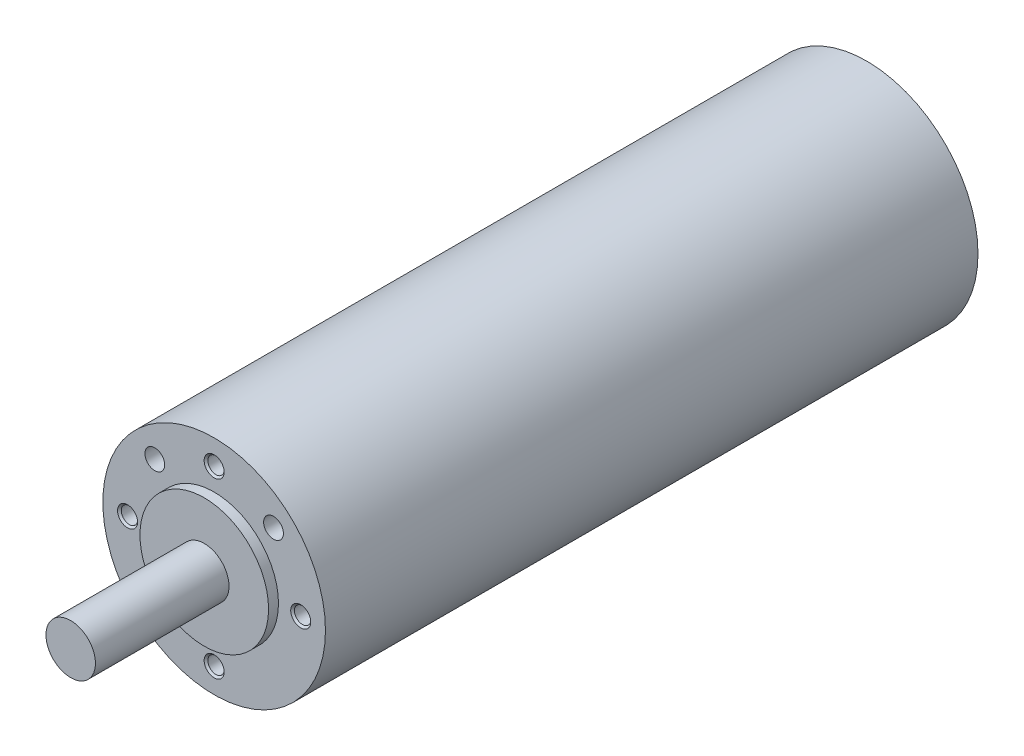
SolidWorks part; units mm, degrees
ref_plane "Front Plane" through (0, 0, 0) normal (0, 0, 1) x (1, 0, 0)
ref_plane "Top Plane" through (0, 0, 0) normal (0, 1, 0) x (1, 0, 0)
ref_plane "Right Plane" through (0, 0, 0) normal (1, 0, 0) x (0, 0, -1)
sketch "Sketch1" plane through (0, 0, 0) normal (0, 0, 1) x (1, 0, 0)
  circle A0 centre (0, 0) radius 22.5
  dimension "D1" = 45
extrude "Boss-Extrude1" add sketch "Sketch1" against normal blind 131.9
sketch "Sketch2" plane through (0, 0, 0) normal (0, 0, 1) x (1, 0, 0)
  circle A0 centre (0, 0) radius 13
  dimension "D1" = 26
extrude "Boss-Extrude2" add sketch "Sketch2" along normal blind 2
sketch "Sketch3" plane through (0, 0, 2) normal (0, 0, 1) x (1, 0, 0)
  circle A0 centre (0, 0) radius 5
  dimension "D1" = 10
extrude "Boss-Extrude3" add sketch "Sketch3" along normal blind 27
sketch "Sketch4" plane through (0, 0, 0) normal (0, 0, 1) x (1, 0, 0)
  circle A0 centre (0, 0) radius 17.5 construction
  circle A1 centre (0, 17.5) radius 2
  circle A2 centre (0, 0) radius 17.5 construction
  circle A3 centre (0, 0) radius 17.5 construction
  circle A4 centre (0, 0) radius 17.5 construction
  circle A5 centre (17.5, 0) radius 2
  circle A6 centre (0, -17.5) radius 2
  circle A7 centre (-17.5, 0) radius 2
  point P14 (0, 0)
  point P21 (0, 0)
  dimension "D1" = 35
  dimension "D2" = 4
  dimension "D3" = 4
  dimension "D4" = 4
hole_wizard "M4 Tapped Hole1" positions "Sketch5" profile "Sketch6" tap size "M4" standard "ISO"
sketch "Sketch5" plane through (0, 0, 0) normal (0, 0, 1) x (1, 0, 0)
  point P0 (0, 17.5)
  point P3 (-17.5, 0)
  point P6 (0, -17.5)
  point P9 (17.5, 0)
sketch "Sketch6" plane through (0, 17.5, 0) normal (1, 0, 0) x (0, -1, 0)
  line L0 (0, 0) -> (0, 9.9914)
  line L1 (0, 9.9914) -> (1.65, 9)
  line L2 (1.65, 9) -> (1.65, 0.375)
  line L3 (1.65, 0.375) -> (2.025, 0)
  line L5 (2.025, 0) -> (0, 0)
  line L6 (-1.65, 0.375) -> (-2.025, 0) construction
  line L10 (0, 9.9914) -> (-1.65, 9) construction
  line L11 (0, -6.35) -> (0, 107.95) construction
  dimension "Tap Drill Dia." = 3.3
  dimension "Tap Drill Depth" = 9
  dimension "Near C'Sink Dia." = 4.05
  dimension "Near C'Sink Angle" = 90
  dimension "Drill Angle" = 118
cosmetic thread "Hole Thread1" parameters "D1"=8, "D2"=4
cosmetic thread "Hole Thread2" parameters "D1"=8, "D2"=4
cosmetic thread "Hole Thread3" parameters "D1"=8, "D2"=4
cosmetic thread "Hole Thread4" parameters "D1"=8, "D2"=4
sketch "Sketch7" plane through (0, 0, 0) normal (0, 0, 1) x (1, 0, 0)
  circle A2 centre (0, 0) radius 17.5 construction
  circle A3 centre (-12, 12.7377) radius 2
  circle A4 centre (12, 12.7377) radius 2
  dimension "D1" = 35
  dimension "D3" = 4
  dimension "D4" = 4
  dimension "D2" = 12
  dimension "D5" = 12
extrude "Cut-Extrude1" cut sketch "Sketch7" against normal blind 25
